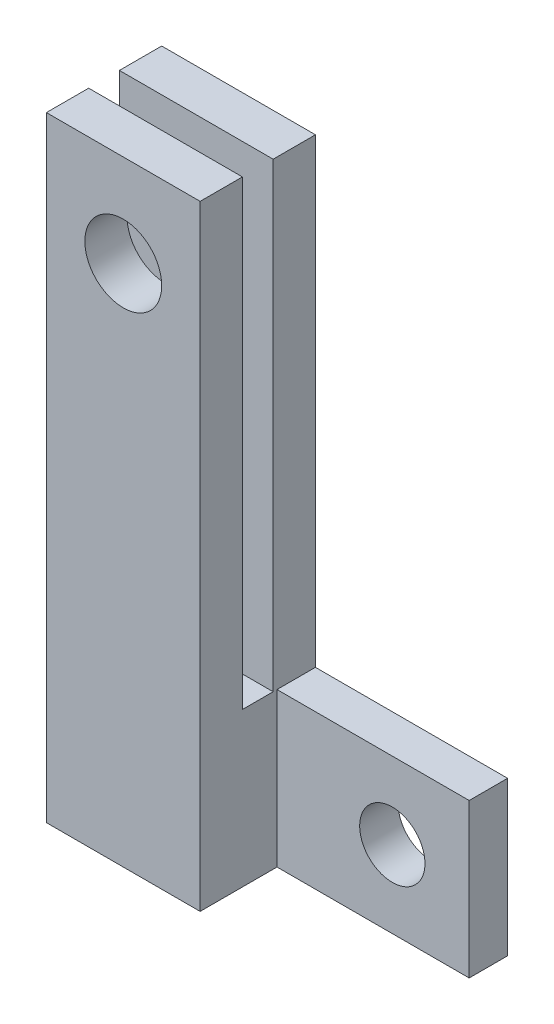
SolidWorks part; units mm, degrees
ref_plane "Front Plane" through (0, 0, 0) normal (0, 0, 1) x (1, 0, 0)
ref_plane "Top Plane" through (0, 0, 0) normal (0, 1, 0) x (1, 0, 0)
ref_plane "Right Plane" through (0, 0, 0) normal (1, 0, 0) x (0, 0, -1)
sketch "Sketch1" plane through (0, 0, 0) normal (0, 0, 1) x (1, 0, 0)
  line L1 (-10, 30.8594) -> (10, 30.8594)
  line L2 (-10, 30.8594) -> (-10, -39.1406)
  line L3 (-10, -39.1406) -> (10, -39.1406)
  line L4 (10, 30.8594) -> (10, -39.1406)
  point P0 (0, 0)
  dimension "D1" = 10
  dimension "D2" = 70
  dimension "D3" = 10
  dimension "D4" = 39.1406
extrude "Boss-Extrude1" add sketch "Sketch1" along normal blind 15
sketch "Sketch2" plane through (0, 30.8594, 0) normal (0, 1, 0) x (1, 0, 0)
  line L0 (10, -15) -> (10, 0) construction
  line L1 (-10, -5.5) -> (10, -5.5)
  line L2 (-10, -5.5) -> (-10, -9.5)
  line L3 (-10, -9.5) -> (10, -9.5)
  line L4 (10, -5.5) -> (10, -9.5)
  line L5 (10, 0) -> (-10, 0) construction
  line L6 (10, -15) -> (-10, -15) construction
  point P0 (-1.25, -7.5)
  dimension "D1" = 5.5
  dimension "D2" = 5.5
  dimension "D3" = 20
  dimension "D4" = 4
extrude "Cut-Extrude1" cut sketch "Sketch2" against normal blind 60
sketch "Sketch3" plane through (0, 0, 15) normal (0, 0, 1) x (1, 0, 0)
  line L1 (10, 30.8594) -> (-10, 30.8594) construction
  circle A0 centre (0, 18.8594) radius 5
  dimension "D1" = 10
  dimension "D3" = 12
extrude "Cut-Extrude2" cut sketch "Sketch3" against normal blind 15
sketch "Sketch4" plane through (0, 0, 0) normal (0, 0, -1) x (-1, 0, 0)
  line L0 (10, -39.1406) -> (-10, -39.1406) construction
  line L1 (-10, -39.1406) -> (-10, 30.8594) construction
  line L3 (10, -49.1406) -> (10, -29.1406)
  line L4 (10, -29.1406) -> (-35, -29.1406)
  line L5 (-35, -29.1406) -> (-35, -49.1406)
  line L6 (-35, -49.1406) -> (10, -49.1406)
  point P10 (10, -39.1406)
  dimension "D1" = 45
  dimension "D2" = 20
extrude "Boss-Extrude2" add sketch "Sketch4" against normal blind 5
sketch "Sketch7" plane through (0, 0, 0) normal (0, 0, -1) x (-1, 0, 0)
  line L0 (-10, -29.1228) -> (44.5945, -29.1228) construction
  line L1 (-10, -29.1406) -> (-10, 30.8594) construction
  line L2 (10, 30.8594) -> (10, -39.1406) construction
  circle A0 centre (-25, -39.1228) radius 4.25
  dimension "D1" = 8.5
  dimension "D2" = 10
  dimension "D3" = 35
extrude "Cut-Extrude4" cut sketch "Sketch7" against normal blind 8
sketch "Sketch8" plane through (0, 0, 5) normal (0, 0, 1) x (1, 0, 0)
  line L0 (-10, -39.1406) -> (-10, -49.1406)
  line L1 (-10, -39.1406) -> (10, -39.1406)
  line L2 (10, -39.1406) -> (10, -49.1406)
  line L3 (35, -49.1406) -> (-10, -49.1406) construction
  line L4 (10, -49.1406) -> (-10, -49.1406)
extrude "Boss-Extrude3" add sketch "Sketch8" along normal blind 10
sketch "Sketch9" plane through (0, 0, 0) normal (0, 0, -1) x (-1, 0, 0)
  line L0 (-25, -39.1228) -> (10, -39.1228) construction
  line L1 (10, 30.8594) -> (10, -49.1406) construction
  line L2 (10, -45.1228) -> (5, -45.1228)
  line L3 (5, -45.1228) -> (5, -33.1228)
  line L4 (5, -33.1228) -> (10, -33.1228)
  line L5 (10, -33.1228) -> (10, -45.1228)
  point P9 (7.5, -33.1228)
  dimension "D1" = 6
  dimension "D2" = 12
  dimension "D3" = 6
  dimension "D4" = 5
extrude "Cut-Extrude5" cut sketch "Sketch9" against normal blind 10
sketch "Sketch10" plane through (-10, 0, 0) normal (-1, 0, 0) x (0, 0, 1)
  line L0 (0, -31.1228) -> (12, -31.1228)
  line L1 (0, 30.8594) -> (0, -33.1228) construction
  line L2 (12, -31.1228) -> (12, -47.1228)
  line L3 (12, -47.1228) -> (0, -47.1228)
  line L4 (0, -45.1228) -> (0, -49.1406) construction
  line L5 (0, -47.1228) -> (0, -31.1228)
  line L6 (10, -33.1228) -> (0, -33.1228) construction
  line L7 (10, -45.1228) -> (10, -33.1228) construction
  line L8 (10, -45.1228) -> (0, -45.1228) construction
  dimension "D1" = 2
  dimension "D2" = 2
  dimension "D3" = 2
extrude "Boss-Extrude4" add sketch "Sketch10" along normal blind 1
